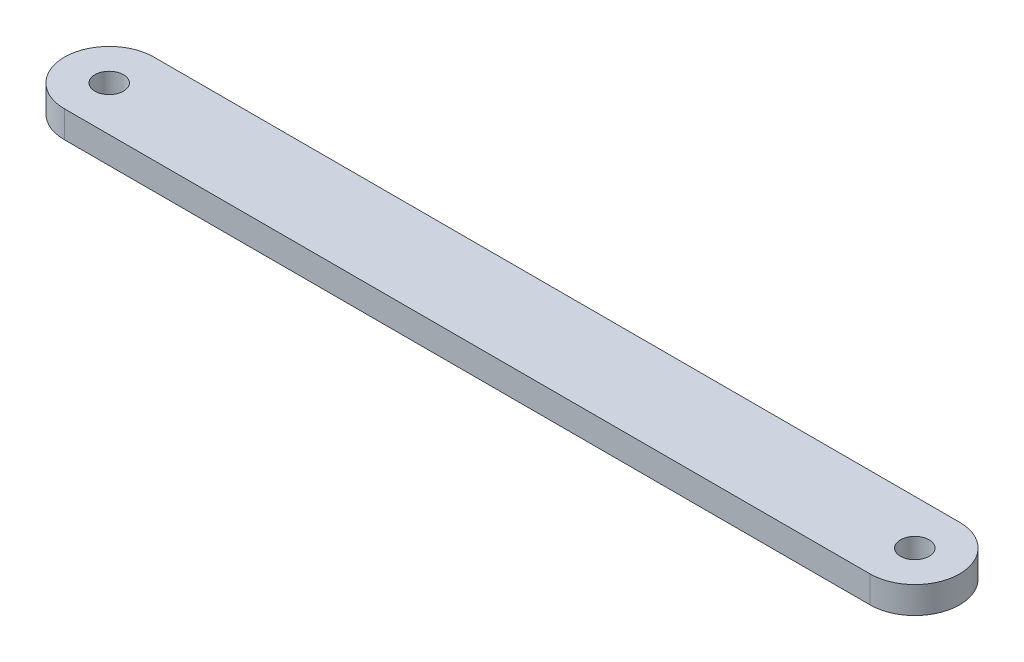
SolidWorks part; units mm, degrees
ref_plane "正面" through (0, 0, 0) normal (0, 0, 1) x (1, 0, 0)
ref_plane "平面" through (0, 0, 0) normal (0, 1, 0) x (1, 0, 0)
ref_plane "右側面" through (0, 0, 0) normal (1, 0, 0) x (0, 0, -1)
sketch "ｽｹｯﾁ1" plane through (0, 0, 0) normal (0, 1, 0) x (1, 0, 0)
  line L0 (0, 0) -> (110, 0) construction
  line L1 (0, -5) -> (90, -5)
  line L3 (0, 5) -> (90, 5)
  circle A0 centre (0, 0) radius 1.6
  circle A1 centre (90, 0) radius 1.6
  arc A2 (0, 5) -> (0, -5) centre (0, 0) ccw
  arc A3 (90, -5) -> (90, 5) centre (90, 0) ccw
  point P1 (0, 0)
  dimension "D5" = 3.2
  dimension "D1" = 5
  dimension "D2" = 10
  dimension "D4" = 90
extrude "ﾎﾞｽ - 押し出し1" add sketch "ｽｹｯﾁ1" along normal blind 3
